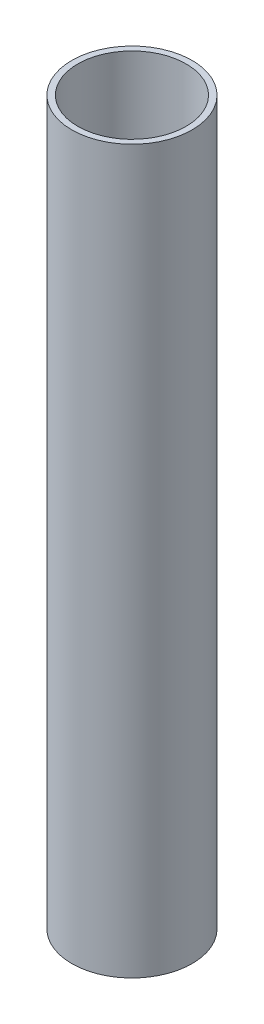
SolidWorks part; units mm, degrees
ref_plane "Front Plane" through (0, 0, 0) normal (0, 0, 1) x (1, 0, 0)
ref_plane "Top Plane" through (0, 0, 0) normal (0, 1, 0) x (1, 0, 0)
ref_plane "Right Plane" through (0, 0, 0) normal (1, 0, 0) x (0, 0, -1)
sketch "Sketch1" plane through (0, 0, 0) normal (0, 1, 0) x (1, 0, 0)
  circle A0 centre (0, 0) radius 1
  circle A1 centre (0, 0) radius 0.9
  dimension "D1" = 2
  dimension "D2" = 0.1
extrude "Boss-Extrude1" add sketch "Sketch1" along normal blind 12
